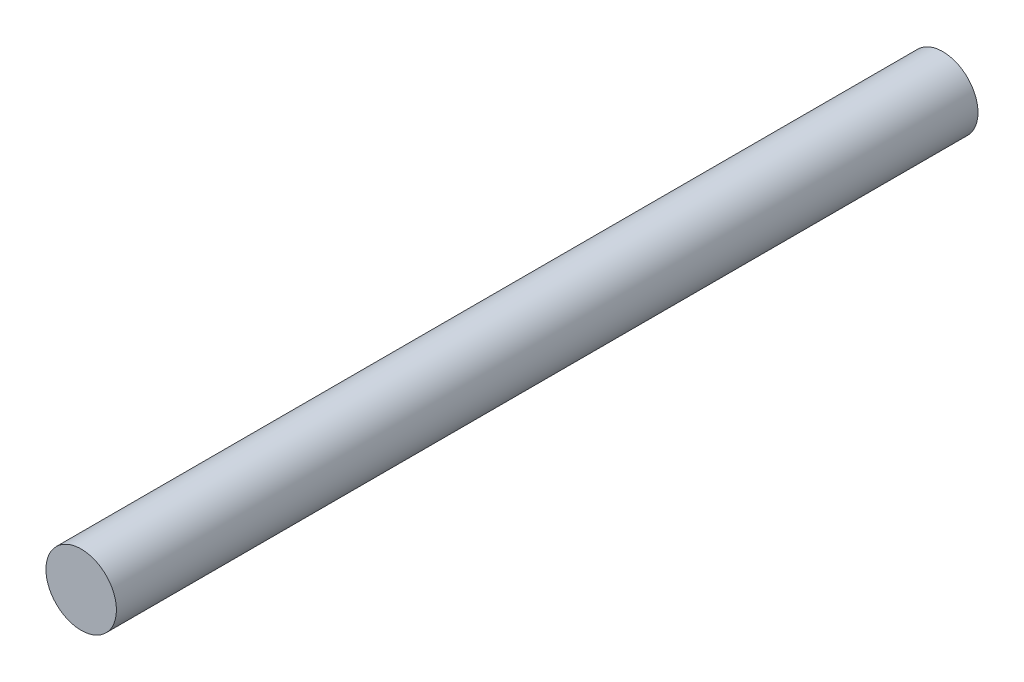
SolidWorks part; units mm, degrees
ref_plane "Front Plane" through (0, 0, 0) normal (0, 0, 1) x (1, 0, 0)
ref_plane "Top Plane" through (0, 0, 0) normal (0, 1, 0) x (1, 0, 0)
ref_plane "Right Plane" through (0, 0, 0) normal (1, 0, 0) x (0, 0, -1)
sketch "Sketch1" plane through (0, 0, 0) normal (0, 0, 1) x (1, 0, 0)
  circle A0 centre (0, 0) radius 4.5
  dimension "D1" = 9
extrude "Boss-Extrude1" add sketch "Sketch1" along normal blind 110
